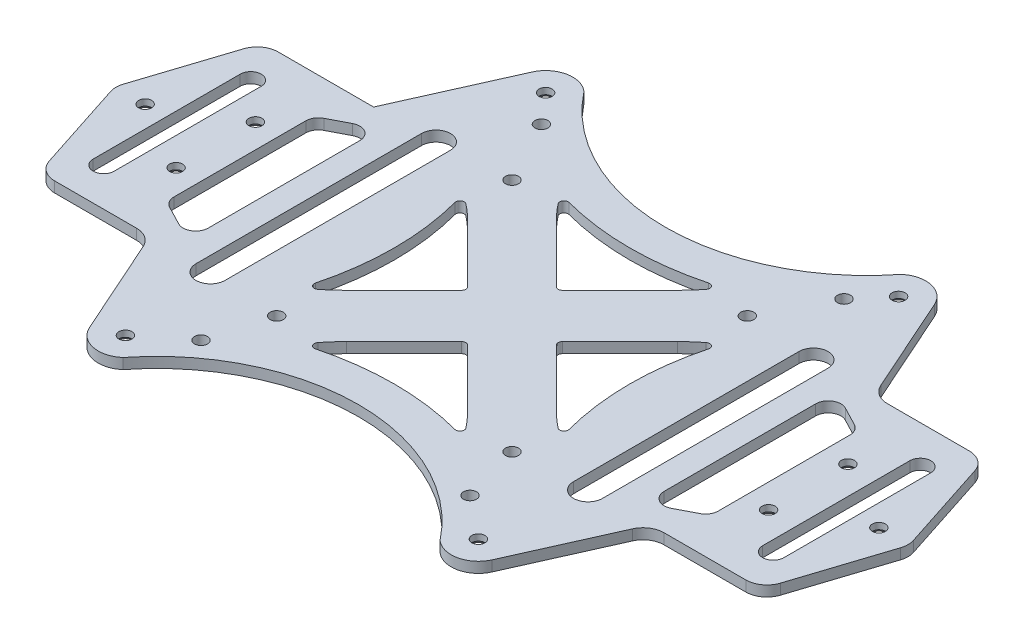
SolidWorks part; units mm, degrees
material "PPS"
ref_plane "前视基准面" through (0, 0, 0) normal (0, 0, 1) x (1, 0, 0)
ref_plane "上视基准面" through (0, 0, 0) normal (0, 1, 0) x (1, 0, 0)
ref_plane "右视基准面" through (0, 0, 0) normal (1, 0, 0) x (0, 0, -1)
sketch "参考" plane through (0, 0, 0) normal (0, 1, 0) x (1, 0, 0)
  line L3 (-133.7177, 0) -> (146.3754, 0) construction
  line L56 (0, 96.0639) -> (0, -115.1457) construction
  line L177 (114.5911, 7.4683) -> (114.5911, -7.4683)
  line L178 (114.5911, 7.4683) -> (43.1936, 17.6463)
  line L179 (114.5911, -7.4683) -> (43.1936, -17.6463)
  line L180 (-114.5911, -7.4683) -> (-43.1936, -17.6463)
  line L181 (-114.5911, 7.4683) -> (-114.5911, -7.4683)
  line L182 (-114.5911, 7.4683) -> (-43.1936, 17.6463)
  arc A18 (-37.7098, 54.831) -> (37.7098, 54.831) centre (0, 111.5317) ccw
  arc A20 (48.2756, 48.4632) -> (43.1936, 17.6463) centre (246.1791, 0) ccw
  arc A21 (48.2756, 48.4632) -> (37.7098, 54.831) centre (42, 50) ccw
  arc A22 (-37.7098, -54.831) -> (37.7098, -54.831) centre (0, -111.5317) cw
  arc A23 (48.2756, -48.4632) -> (43.1936, -17.6463) centre (246.1791, 0) cw
  arc A24 (48.2756, -48.4632) -> (37.7098, -54.831) centre (42, -50) cw
  arc A26 (-48.2756, -48.4632) -> (-37.7098, -54.831) centre (-42, -50) ccw
  arc A27 (-48.2756, -48.4632) -> (-43.1936, -17.6463) centre (-246.1791, 0) ccw
  arc A28 (-48.2756, 48.4632) -> (-37.7098, 54.831) centre (-42, 50) cw
  arc A30 (-48.2756, 48.4632) -> (-43.1936, 17.6463) centre (-246.1791, 0) cw
  dimension "D11" = 50
  dimension "D12" = 42
sketch "草图1" plane through (0, 0, 0) normal (0, 1, 0) x (1, 0, 0)
  line L0 (-160.1541, 0) -> (172.3115, 0) construction
  line L1 (0, 124.2182) -> (0, 50.8906) construction
  line L2 (79.6696, -17.5) -> (79.6696, 17.5) construction
  line L3 (77.1696, -17.5) -> (77.1696, 17.5)
  line L4 (82.1696, -17.5) -> (82.1696, 17.5)
  line L5 (-133.7177, 0) -> (146.3754, 0) construction
  line L6 (47.9, 52.6334) -> (59.525, 26.5883)
  line L7 (59.525, 26.5883) -> (85.8696, 26.5883)
  line L8 (85.8696, 26.5883) -> (94.5058, 0)
  line L9 (59.525, -26.5883) -> (85.8696, -26.5883)
  line L10 (47.9, -52.6334) -> (59.525, -26.5883)
  line L11 (85.8696, -26.5883) -> (94.5058, 0)
  line L12 (-47.9, -52.6334) -> (-59.525, -26.5883)
  line L13 (-59.525, -26.5883) -> (-85.8696, -26.5883)
  line L14 (-85.8696, -26.5883) -> (-94.5058, 0)
  line L15 (-85.8696, 26.5883) -> (-94.5058, 0)
  line L16 (-47.9, 52.6334) -> (-59.525, 26.5883)
  line L17 (-59.525, 26.5883) -> (-85.8696, 26.5883)
  line L18 (-79.6696, -17.5) -> (-79.6696, 17.5) construction
  line L19 (-77.1696, -17.5) -> (-77.1696, 17.5)
  line L20 (-82.1696, -17.5) -> (-82.1696, 17.5)
  line L21 (-24.996, 14.4296) -> (-10.5664, 0)
  line L22 (14.4296, 24.996) -> (0, 10.5664)
  line L23 (-24.996, -14.4296) -> (-10.5664, 0)
  line L24 (-14.4296, 24.996) -> (0, 10.5664)
  line L25 (0, 96.0639) -> (0, -115.1457) construction
  line L26 (24.996, -14.4296) -> (10.5664, 0)
  line L27 (24.996, 14.4296) -> (10.5664, 0)
  line L28 (-14.4296, -24.996) -> (0, -10.5664)
  line L29 (14.4296, -24.996) -> (0, -10.5664)
  line L30 (44.9192, -26.8293) -> (44.9192, 26.8293) construction
  line L31 (41.4687, -26.8293) -> (41.4687, 26.8293)
  line L32 (48.3697, -26.8293) -> (48.3697, 26.8293)
  line L39 (-44.9192, -26.8293) -> (-44.9192, 26.8293) construction
  line L40 (-41.4687, -26.8293) -> (-41.4687, 26.8293)
  line L41 (-48.3697, -26.8293) -> (-48.3697, 26.8293)
  line L48 (0, -50.8906) -> (0, -143.4382) construction
  line L53 (0, 44.9191) -> (0, -44.9191) construction
  circle A6 centre (42, 50) radius 1.55
  circle A7 centre (42, -50) radius 1.55
  circle A8 centre (-42, -50) radius 1.55
  circle A9 centre (-42, 50) radius 1.55
  circle A10 centre (36, 43) radius 1.55
  circle A11 centre (32, -42) radius 1.55
  circle A12 centre (-32, -42) radius 1.55
  circle A13 centre (-36, 43) radius 1.55
  arc A18 (77.1696, -17.5) -> (82.1696, -17.5) centre (79.6696, -17.5) ccw
  arc A19 (82.1696, 17.5) -> (77.1696, 17.5) centre (79.6696, 17.5) ccw
  circle A20 centre (70.5, 9.4358) radius 1.55
  circle A21 centre (70.5, -9.4358) radius 1.55
  circle A22 centre (-70.5, -9.4358) radius 1.55
  circle A23 centre (-70.5, 9.4358) radius 1.55
  circle A24 centre (87.3, 0) radius 1.55
  arc A25 (48.2756, 48.4632) -> (37.7098, 54.831) centre (42, 50) ccw construction
  arc A29 (-77.1696, -17.5) -> (-82.1696, -17.5) centre (-79.6696, -17.5) cw
  arc A30 (-82.1696, 17.5) -> (-77.1696, 17.5) centre (-79.6696, 17.5) cw
  circle A31 centre (-87.3, 0) radius 1.55
  arc A33 (-24.996, 14.4296) -> (-30.9782, 19.3706) centre (-53.9062, -14.4807) ccw
  arc A34 (-24.996, -14.4296) -> (-30.9782, -19.3706) centre (-53.9062, 14.4807) cw
  arc A35 (-30.9782, -19.3706) -> (-30.9782, 19.3706) centre (-93.0146, 0) ccw
  arc A36 (-14.4296, 24.996) -> (-19.3706, 30.9782) centre (14.4807, 53.9062) cw
  arc A37 (-19.3706, 30.9782) -> (19.3706, 30.9782) centre (0, 93.0146) ccw
  arc A38 (14.4296, 24.996) -> (19.3706, 30.9782) centre (-14.4807, 53.9062) ccw
  arc A39 (24.996, 14.4296) -> (30.9782, 19.3706) centre (53.9062, -14.4807) cw
  arc A40 (30.9782, 19.3706) -> (30.9782, -19.3706) centre (93.0146, 0) ccw
  arc A41 (24.996, -14.4296) -> (30.9782, -19.3706) centre (53.9062, 14.4807) ccw
  arc A42 (14.4296, -24.996) -> (19.3706, -30.9782) centre (-14.4807, -53.9062) cw
  arc A43 (19.3706, -30.9782) -> (-19.3706, -30.9782) centre (0, -93.0146) ccw
  arc A44 (-14.4296, -24.996) -> (-19.3706, -30.9782) centre (14.4807, -53.9062) ccw
  arc A45 (41.4687, -26.8293) -> (48.3697, -26.8293) centre (44.9192, -26.8293) ccw
  arc A46 (48.3697, 26.8293) -> (41.4687, 26.8293) centre (44.9192, 26.8293) ccw
  arc A51 (-41.4687, -26.8293) -> (-48.3697, -26.8293) centre (-44.9192, -26.8293) cw
  arc A52 (-48.3697, 26.8293) -> (-41.4687, 26.8293) centre (-44.9192, 26.8293) cw
  circle A55 centre (28, 28) radius 1.55
  circle A56 centre (28, -28) radius 1.55
  circle A57 centre (-28, -28) radius 1.55
  circle A58 centre (-28, 28) radius 1.55
  arc A59 (37.7098, 54.831) -> (-37.7098, 54.831) centre (0, 84.529) cw
  arc A60 (37.7098, 54.831) -> (47.9, 52.6334) centre (42, 50) cw
  arc A61 (-37.7098, 54.831) -> (-47.9, 52.6334) centre (-42, 50) ccw
  arc A62 (-37.7098, -54.831) -> (-47.9, -52.6334) centre (-42, -50) cw
  arc A63 (37.7098, -54.831) -> (47.9, -52.6334) centre (42, -50) ccw
  arc A64 (37.7098, -54.831) -> (-37.7098, -54.831) centre (0, -84.529) ccw
  point P30 (79.6696, 0)
  point P63 (44.9192, 0)
  point P78 (-79.6696, 0)
  point P98 (0, 0)
  point P136 (-44.9192, 0)
  dimension "D1" = 50
  dimension "D3" = 3.1
  dimension "D8" = 2.5
  dimension "D10" = 3.1
  dimension "D12" = 3.1
  dimension "D15" = 48
  dimension "D18" = 3.1
  dimension "D19" = 28
  dimension "D2" = 42
  dimension "D4" = 36
  dimension "D5" = 32
  dimension "D6" = 42
  dimension "D7" = 43
  dimension "D9" = 35
  dimension "D11" = 70.5
  dimension "D13" = 87.3
  dimension "D14" = 4
  dimension "D20" = 28
  dimension "D21" = 4
extrude "凸台-拉伸1" add sketch "草图1" along normal blind 2.5
chamfer "倒角2" distance 1 angle 45 10 edges at (-70.5, 0, 10.9858) (-70.5, 0, -10.9858) (70.5, 0, 7.8858) (70.5, 0, -7.8858) (-87.3, 0, -1.55) (87.3, 0, 1.55) (-42, 0, 51.55) (42, 0, 48.45) (-42, 0, -51.55) (42, 0, -48.45)
sketch "减重草图镂空-如果影响结构强度则取消" plane through (0, 0, 0) normal (0, -1, 0) x (1, 0, 0)
  line L0 (0, 0) -> (0, 77.9145) construction
  line L1 (0, 0) -> (127.571, 0) construction
  line L2 (-64.75, 17.5) -> (-54.25, 22.966)
  line L3 (-54.25, 22.966) -> (-54.25, -22.966)
  line L4 (-54.25, -22.966) -> (-64.75, -17.5)
  line L5 (-64.75, -17.5) -> (-64.75, 17.5)
  line L6 (54.25, -22.966) -> (64.75, -17.5)
  line L7 (54.25, 22.966) -> (54.25, -22.966)
  line L8 (64.75, 17.5) -> (54.25, 22.966)
  line L9 (64.75, -17.5) -> (64.75, 17.5)
  circle A1 centre (-70.5, 9.4358) radius 1.55 construction
  dimension "D1" = 5.75
  dimension "D2" = 54.25
  dimension "D3" = 62.5
  dimension "D4" = 17.5
extrude "减重-如果影响结构强度则取消" cut sketch "减重草图镂空-如果影响结构强度则取消" against normal through all
fillet "圆角2" radius 3 8 edges at (64.75, 1.25, 17.5) (64.75, 1.25, -17.5) (54.25, 1.25, -22.966) (54.25, 1.25, 22.966) (-54.25, 1.25, -22.966) (-64.75, 1.25, -17.5) (-64.75, 1.25, 17.5) (-54.25, 1.25, 22.966)
fillet "圆角3" radius 5 9 edges at (59.525, 1.25, -26.5883) (85.8696, 1.25, -26.5883) (94.5058, 1.25, 0) (85.8696, 1.25, 26.5883) (59.525, 1.25, 26.5883) (-59.525, 1.25, 26.5883) (-85.8696, 1.25, -26.5883) (-94.5058, 1.25, 0) (-85.8696, 1.25, 26.5883)
fillet "圆角4" radius 1 12 edges at (0, 1.25, -10.5664) (-19.3706, 1.25, 30.9782) (-30.9782, 1.25, 19.3706) (-10.5664, 1.25, 0) (0, 1.25, 10.5664) (-30.9782, 1.25, -19.3706) (19.3706, 1.25, 30.9782) (30.9782, 1.25, 19.3706) (10.5664, 1.25, 0) (-19.3706, 1.25, -30.9782) (19.3706, 1.25, -30.9782) (30.9782, 1.25, -19.3706)
